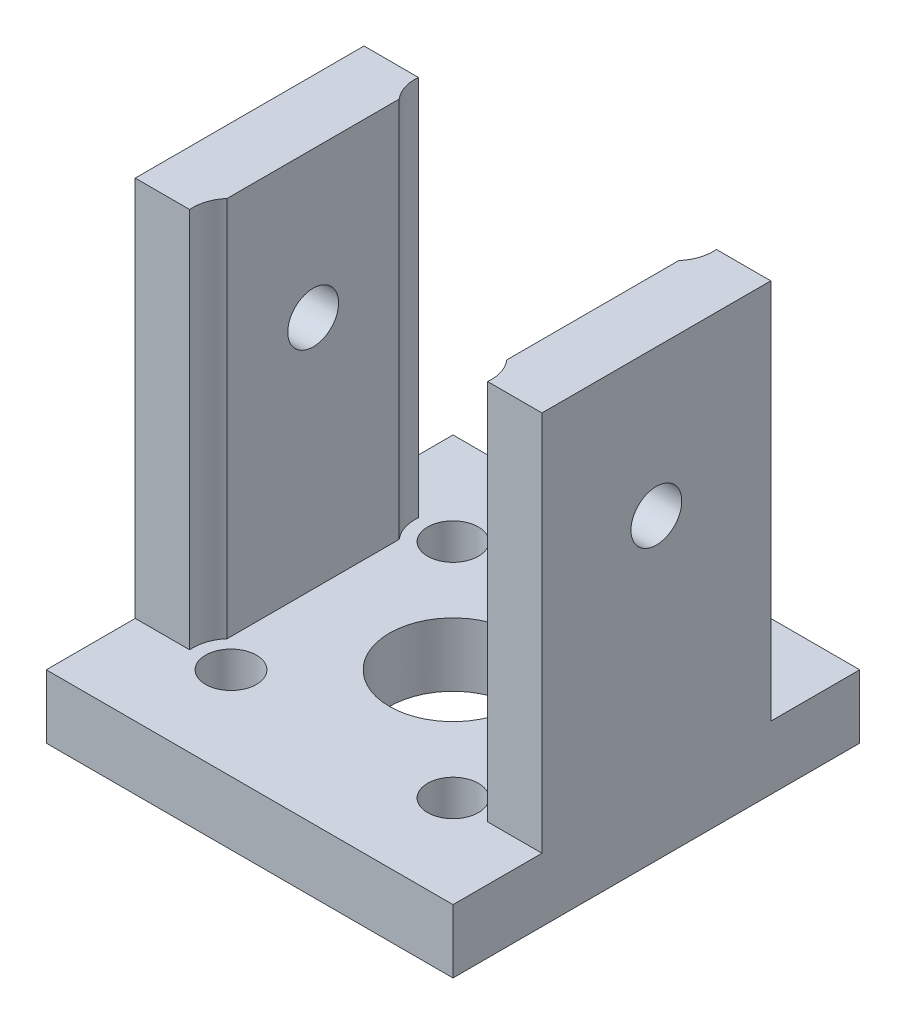
SolidWorks part; units mm, degrees
ref_plane "Front Plane" through (0, 0, 0) normal (0, 0, 1) x (1, 0, 0)
ref_plane "Top Plane" through (0, 0, 0) normal (0, 1, 0) x (1, 0, 0)
ref_plane "Right Plane" through (0, 0, 0) normal (1, 0, 0) x (0, 0, -1)
sketch "Sketch1" plane through (0, 0, 0) normal (0, 1, 0) x (1, 0, 0)
  line L1 (-16, 0) -> (16, 0)
  line L2 (-16, 0) -> (-16, -32)
  line L3 (-16, -32) -> (16, -32)
  line L4 (16, 0) -> (16, -32)
  dimension "D1" = 32
extrude "Boss-Extrude1" add sketch "Sketch1" along normal blind 5
sketch "Sketch2" plane through (0, 5, 0) normal (0, 1, 0) x (1, 0, 0)
  line L0 (-16, 0) -> (-16, -32) construction
  line L1 (-16, -7) -> (-11.7208, -7)
  line L2 (-16, -7) -> (-16, -25)
  line L3 (-16, -25) -> (-11.7212, -25)
  line L4 (-11, -9.2318) -> (-11, -22.7726)
  line L5 (0, 0) -> (0, -32) construction
  line L6 (16, 0) -> (-16, 0) construction
  line L7 (-16, -32) -> (16, -32) construction
  line L8 (16, -25) -> (11.7257, -25)
  line L9 (11, -9.237) -> (11, -22.7675)
  line L10 (16, -7) -> (11.7253, -7)
  line L11 (16, -7) -> (16, -25)
  circle A0 centre (-8.7328, -24.7328) radius 1.5 construction
  circle A1 centre (8.7328, -24.7328) radius 1.5 construction
  circle A2 centre (8.7328, -7.2672) radius 1.5 construction
  circle A3 centre (-8.7328, -7.2672) radius 1.5 construction
  circle A4 centre (-8.7328, -24.7328) radius 1.5 construction
  circle A5 centre (8.7328, -24.7328) radius 1.5 construction
  circle A6 centre (8.7328, -7.2672) radius 1.5 construction
  circle A7 centre (-8.7328, -7.2672) radius 1.5 construction
  arc A8 (-11.7208, -7) -> (-11, -9.2318) centre (-8.7328, -7.2672) ccw
  arc A9 (11, -9.237) -> (11.7253, -7) centre (8.7372, -7.2672) ccw
  arc A10 (11.7257, -25) -> (11, -22.7675) centre (8.7372, -24.7372) ccw
  arc A11 (-11, -22.7726) -> (-11.7212, -25) centre (-8.7328, -24.7372) ccw
  point P12 (-16, -16)
  point P13 (0, -16)
  dimension "D2" = 6
  dimension "D3" = 2
  dimension "D1" = 18
  dimension "D4" = 2
extrude "Boss-Extrude2" add sketch "Sketch2" along normal blind 30
sketch "Sketch3" plane through (0, 0, 0) normal (0, -1, 0) x (1, 0, 0)
  line L4 (-16, 32) -> (-16, 0)
  line L5 (-16, 0) -> (16, 0)
  line L6 (16, 0) -> (16, 32)
  line L7 (16, 32) -> (-16, 32)
  line L8 (-16, 32) -> (-16, 0) construction
  line L9 (-16, 0) -> (16, 0) construction
  line L10 (16, 0) -> (16, 32) construction
  line L11 (16, 32) -> (-16, 32) construction
  circle A0 centre (0, 16) radius 5
  circle A9 centre (-8.7328, 7.2672) radius 2
  circle A10 centre (-8.7328, 24.7328) radius 2
  circle A11 centre (8.7328, 24.7328) radius 2
  circle A12 centre (8.7328, 7.2672) radius 2
  point P2 (0, 0)
  point P5 (0, 0)
  point P7 (0, 14.31)
  point P9 (8.8317, 14.7454)
  point P10 (-16, 16)
  point P11 (0, 0)
  point P12 (0, 32)
  dimension "D1" = 0
  dimension "D2" = 10
extrude "Cut-Extrude1" cut sketch "Sketch3" against normal blind 10
sketch "Sketch4" plane through (-16, 0, 0) normal (-1, 0, 0) x (0, 0, 1)
  line L0 (7, 23.5) -> (25, 23.5) construction
  line L2 (7, 35) -> (25, 35) construction
  line L3 (25, 35) -> (25, 5) construction
  line L4 (7, 35) -> (7, 5) construction
  circle A0 centre (16, 23.5) radius 2
  dimension "D1" = 11.5
extrude "Cut-Extrude2" cut sketch "Sketch4" against normal through all
